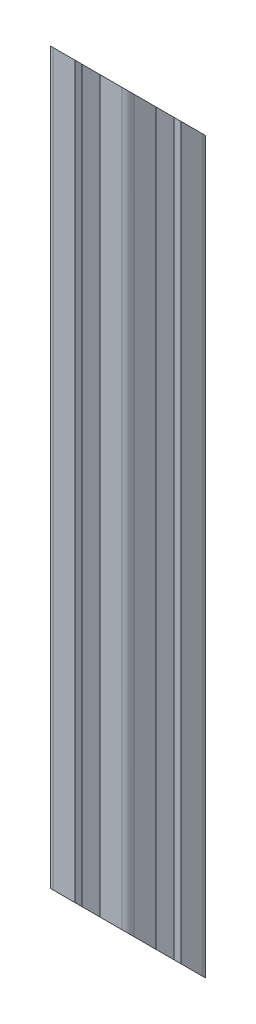
SolidWorks part; units mm, degrees
ref_plane "前视基准面" through (0, 0, 0) normal (0, 0, 1) x (1, 0, 0)
ref_plane "上视基准面" through (0, 0, 0) normal (0, 1, 0) x (1, 0, 0)
ref_plane "右视基准面" through (0, 0, 0) normal (1, 0, 0) x (0, 0, -1)
sketch "草图1" plane through (0, 0, 0) normal (0, 1, 0) x (1, 0, 0)
  line L0 (-22.6856, -15.6919) -> (-20.8856, -15.6919)
  line L1 (-21.1856, -2.5919) -> (-4.1856, -2.5919)
  line L2 (-22.6856, -4.0919) -> (-22.6856, -21.0919)
  line L3 (-21.1856, -22.5919) -> (-4.1856, -22.5919)
  line L4 (-2.6856, -4.0919) -> (-2.6856, -21.0919)
  line L5 (-22.6856, -2.5919) -> (-2.6856, -22.5919) construction
  line L6 (-22.6856, -22.5919) -> (-2.6856, -2.5919) construction
  line L7 (-15.7397, -9.4919) -> (-9.6315, -9.4919)
  line L8 (-15.7397, -9.4919) -> (-15.7397, -15.6919)
  line L9 (-15.7397, -15.6919) -> (-9.6315, -15.6919)
  line L10 (-9.6315, -9.4919) -> (-9.6315, -15.6919)
  line L11 (-15.7397, -9.4919) -> (-9.6315, -15.6919) construction
  line L12 (-15.7397, -15.6919) -> (-9.6315, -9.4919) construction
  line L13 (-20.8856, -15.6919) -> (-20.8856, -18.0919)
  line L14 (-20.8856, -18.0919) -> (-19.0826, -18.0919)
  line L15 (-19.0826, -18.0919) -> (-15.7397, -14.749)
  line L16 (-18.1856, -6.1949) -> (-14.8427, -9.5378)
  line L17 (-18.1856, -4.3919) -> (-18.1856, -6.1949)
  line L18 (-15.7856, -4.3919) -> (-18.1856, -4.3919)
  line L19 (-15.7856, -2.5919) -> (-15.7856, -4.3919)
  line L20 (-6.2885, -7.0919) -> (-9.6315, -10.4349)
  line L21 (-4.4856, -7.0919) -> (-6.2885, -7.0919)
  line L22 (-4.4856, -9.4919) -> (-4.4856, -7.0919)
  line L23 (-2.6856, -9.4919) -> (-4.4856, -9.4919)
  line L24 (-7.1856, -18.989) -> (-10.5285, -15.6461)
  line L25 (-7.1856, -20.7919) -> (-7.1856, -18.989)
  line L26 (-9.5856, -20.7919) -> (-7.1856, -20.7919)
  line L27 (-9.5856, -22.5919) -> (-9.5856, -20.7919)
  line L28 (-15.7856, -22.5919) -> (-15.7856, -20.7919)
  line L29 (-15.7856, -20.7919) -> (-18.1856, -20.7919)
  line L30 (-18.1856, -20.7919) -> (-18.1856, -18.989)
  line L31 (-18.1856, -18.989) -> (-14.8427, -15.6461)
  line L32 (-20.8856, -7.0919) -> (-19.0826, -7.0919)
  line L33 (-19.0826, -7.0919) -> (-15.7397, -10.4349)
  line L34 (-20.8856, -9.4919) -> (-20.8856, -7.0919)
  line L35 (-22.6856, -9.4919) -> (-20.8856, -9.4919)
  line L36 (-7.1856, -4.3919) -> (-7.1856, -6.1949)
  line L37 (-7.1856, -6.1949) -> (-10.5285, -9.5378)
  line L38 (-9.5856, -4.3919) -> (-7.1856, -4.3919)
  line L39 (-9.5856, -2.5919) -> (-9.5856, -4.3919)
  line L40 (-4.4856, -18.0919) -> (-6.2885, -18.0919)
  line L41 (-6.2885, -18.0919) -> (-9.6315, -14.749)
  line L42 (-4.4856, -15.6919) -> (-4.4856, -18.0919)
  line L43 (-2.6856, -15.6919) -> (-4.4856, -15.6919)
  circle A0 centre (-12.6856, -12.5919) radius 2.5
  arc A1 (-22.6856, -4.0919) -> (-21.1856, -2.5919) centre (-21.1856, -4.0919) cw
  arc A2 (-22.6856, -21.0919) -> (-21.1856, -22.5919) centre (-21.1856, -21.0919) ccw
  arc A3 (-4.1856, -2.5919) -> (-2.6856, -4.0919) centre (-4.1856, -4.0919) cw
  arc A4 (-2.6856, -21.0919) -> (-4.1856, -22.5919) centre (-4.1856, -21.0919) cw
  point P0 (-12.6856, -12.5919)
  point P19 (-12.6856, -12.5919)
  point P25 (-12.6856, -12.5919)
  point P31 (-12.6856, -12.5919)
  point P37 (-12.6856, -12.5919)
  point P59 (-12.6856, -12.5919)
extrude "凸台-拉伸1" add sketch "草图1" along normal blind 200
sketch "草图4" plane through (-22.6856, 0, 0) normal (-1, 0, 0) x (0, 0, 1)
  line L0 (22.5919, 200) -> (2.5919, 180)
  line L1 (2.5919, 200) -> (2.5919, 0) construction
  line L2 (22.5919, 200) -> (22.5919, 0) construction
  line L3 (2.5919, 180) -> (2.5919, 200)
  line L4 (2.5919, 200) -> (22.5919, 200)
  dimension "D1" = 45
extrude "切除-拉伸6" cut sketch "草图4" against normal blind 90
sketch "草图5" plane through (-22.6856, 0, 0) normal (-1, 0, 0) x (0, 0, 1)
  line L0 (2.5919, 0) -> (22.5919, 20)
  line L1 (22.5919, 200) -> (22.5919, 0) construction
  line L2 (10.4349, 0) -> (14.749, 0) construction
  line L3 (22.5919, 20) -> (22.5919, 0)
  line L4 (22.5919, 0) -> (2.5919, 0)
  dimension "D1" = 45
extrude "切除-拉伸7" cut sketch "草图5" against normal through all
